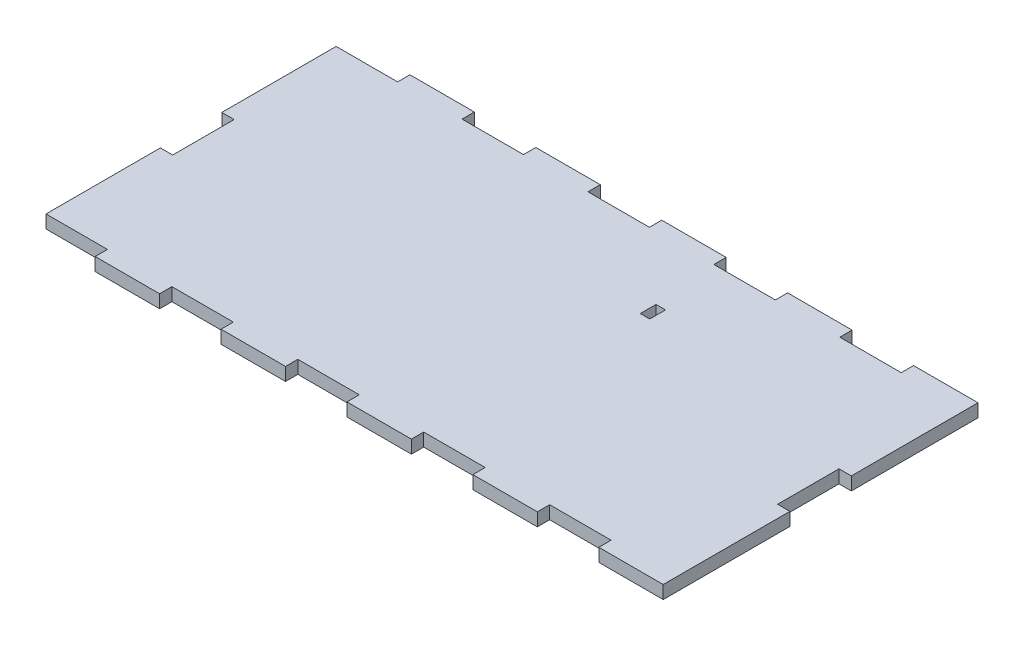
SolidWorks part; units mm, degrees
ref_plane "Front Plane" through (0, 0, 0) normal (0, 0, 1) x (1, 0, 0)
ref_plane "Top Plane" through (0, 0, 0) normal (0, 1, 0) x (1, 0, 0)
ref_plane "Right Plane" through (0, 0, 0) normal (1, 0, 0) x (0, 0, -1)
sketch "Sketch1" plane through (0, 0, 0) normal (0, 1, 0) x (1, 0, 0)
  line L1 (-100, 50) -> (100, 50)
  line L2 (-100, 50) -> (-100, -50)
  line L3 (-100, -50) -> (100, -50)
  line L4 (100, 50) -> (100, -50)
  line L5 (-100, 50) -> (100, -50) construction
  line L6 (-100, -50) -> (100, 50) construction
  point P0 (0, 0)
  dimension "Length" = 200
  dimension "with" = 100
extrude "Boss-Extrude1" add sketch "Sketch1" along normal blind 4.15
sketch "Sketch3" plane through (0, 4.15, 0) normal (0, 1, 0) x (1, 0, 0)
  line L0 (-100, 46.09) -> (-100, 50)
  line L1 (-100, -50) -> (-80.48, -50)
  line L2 (-100, -50) -> (-100, -46.09)
  line L3 (-100, -46.09) -> (-80.48, -46.09)
  line L4 (-80.48, -50) -> (-80.48, -46.09)
  line L5 (-100, 46.09) -> (-80.48, 46.09)
  line L6 (-80.48, 46.09) -> (-80.48, 50)
  line L7 (-100, 50) -> (-80.48, 50)
  line L8 (-60, 46.09) -> (-60, 50)
  line L9 (-60, 46.09) -> (-40.48, 46.09)
  line L10 (-40.48, 46.09) -> (-40.48, 50)
  line L11 (-60, 50) -> (-40.48, 50)
  line L12 (-20, 46.09) -> (-20, 50)
  line L13 (-20, 46.09) -> (-0.48, 46.09)
  line L14 (-0.48, 46.09) -> (-0.48, 50)
  line L15 (-20, 50) -> (-0.48, 50)
  line L16 (20, 46.09) -> (20, 50)
  line L17 (20, 46.09) -> (39.52, 46.09)
  line L18 (39.52, 46.09) -> (39.52, 50)
  line L19 (20, 50) -> (39.52, 50)
  line L20 (60, 46.09) -> (60, 50)
  line L21 (60, 46.09) -> (79.52, 46.09)
  line L22 (79.52, 46.09) -> (79.52, 50)
  line L23 (60, 50) -> (79.52, 50)
  line L24 (-60, -50) -> (-60, -46.09)
  line L25 (-60, -50) -> (-40.48, -50)
  line L26 (-40.48, -50) -> (-40.48, -46.09)
  line L27 (-60, -46.09) -> (-40.48, -46.09)
  line L28 (-20, -50) -> (-20, -46.09)
  line L29 (-20, -50) -> (-0.48, -50)
  line L30 (-0.48, -50) -> (-0.48, -46.09)
  line L31 (-20, -46.09) -> (-0.48, -46.09)
  line L32 (20, -50) -> (20, -46.09)
  line L33 (20, -50) -> (39.52, -50)
  line L34 (39.52, -50) -> (39.52, -46.09)
  line L35 (20, -46.09) -> (39.52, -46.09)
  line L36 (60, -50) -> (60, -46.09)
  line L37 (60, -50) -> (79.52, -50)
  line L38 (79.52, -50) -> (79.52, -46.09)
  line L39 (60, -46.09) -> (79.52, -46.09)
  line L40 (-100, -50) -> (100, -50) construction
  line L41 (100, 50) -> (-100, 50) construction
  point P5 (-80.48, -48.045)
  dimension "D1" = 3.91
  dimension "D2" = 19.52
  dimension "D5" = 20.48
  dimension "D3" = 2
  dimension "D4" = 5
extrude "Cut-Extrude2" cut sketch "Sketch3" against normal blind 10
sketch "Sketch4" plane through (0, 4.15, 0) normal (0, 1, 0) x (1, 0, 0)
  line L0 (-100, 9.76) -> (-100, -9.76)
  line L1 (-100, 9.76) -> (-96.09, 9.76)
  line L2 (-100, -9.76) -> (-96.09, -9.76)
  line L3 (-96.09, 9.76) -> (-96.09, -9.76)
  line L4 (-100, 46.09) -> (-100, -46.09) construction
  line L5 (0, -2.2825) -> (0, 2.2825) construction
  line L6 (100, -9.76) -> (96.09, -9.76)
  line L7 (96.09, 9.76) -> (96.09, -9.76)
  line L8 (100, 9.76) -> (96.09, 9.76)
  line L9 (100, 9.76) -> (100, -9.76)
  point P6 (-100, 0)
  dimension "D1" = 19.52
  dimension "D2" = 3.91
extrude "Cut-Extrude3" cut sketch "Sketch4" against normal blind 10
sketch "Sketch5" [suppressed] plane through (0, 4.15, 0) normal (0, 1, 0) x (1, 0, 0)
  line L0 (100, -36.09) -> (100, -40)
  line L1 (100, -36.09) -> (80.48, -36.09)
  line L2 (100, -40) -> (80.48, -40)
  line L3 (80.48, -36.09) -> (80.48, -40)
  line L4 (100, -40) -> (100, -9.76) construction
  line L5 (60, -36.09) -> (60, -40)
  line L6 (60, -36.09) -> (40.48, -36.09)
  line L7 (40.48, -36.09) -> (40.48, -40)
  line L8 (60, -40) -> (40.48, -40)
  line L9 (20, -36.09) -> (20, -40)
  line L10 (20, -36.09) -> (0.48, -36.09)
  line L11 (0.48, -36.09) -> (0.48, -40)
  line L12 (20, -40) -> (0.48, -40)
  line L13 (-20, -36.09) -> (-20, -40)
  line L14 (-20, -36.09) -> (-39.52, -36.09)
  line L15 (-39.52, -36.09) -> (-39.52, -40)
  line L16 (-20, -40) -> (-39.52, -40)
  line L17 (-60, -36.09) -> (-60, -40)
  line L18 (-60, -36.09) -> (-79.52, -36.09)
  line L19 (-79.52, -36.09) -> (-79.52, -40)
  line L20 (-60, -40) -> (-79.52, -40)
  line L21 (60, 40) -> (60, 36.09)
  line L22 (60, 40) -> (40.48, 40)
  line L23 (40.48, 40) -> (40.48, 36.09)
  line L24 (60, 36.09) -> (40.48, 36.09)
  line L25 (20, 40) -> (20, 36.09)
  line L26 (20, 40) -> (0.48, 40)
  line L27 (0.48, 40) -> (0.48, 36.09)
  line L28 (20, 36.09) -> (0.48, 36.09)
  line L29 (-20, 40) -> (-20, 36.09)
  line L30 (-20, 40) -> (-39.52, 40)
  line L31 (-39.52, 40) -> (-39.52, 36.09)
  line L32 (-20, 36.09) -> (-39.52, 36.09)
  line L33 (-60, 40) -> (-60, 36.09)
  line L34 (-60, 40) -> (-79.52, 40)
  line L35 (-79.52, 40) -> (-79.52, 36.09)
  line L36 (-60, 36.09) -> (-79.52, 36.09)
  line L37 (100, 40) -> (100, 36.09)
  line L38 (100, 40) -> (80.48, 40)
  line L39 (80.48, 40) -> (80.48, 36.09)
  line L40 (100, 36.09) -> (80.48, 36.09)
  line L41 (100, 40) -> (-100, 40) construction
  point P9 (100, 38.045)
  point P46 (100, -38.045)
  dimension "D1" = 3.91
  dimension "D2" = 19.52
  dimension "D5" = 20.48
  dimension "D3" = 5
  dimension "D4" = 2
extrude "Cut-Extrude4" [suppressed] cut sketch "Sketch5" against normal blind 10
sketch "Sketch6" [suppressed] plane through (0, 4.15, 0) normal (0, 1, 0) x (1, 0, 0)
  line L4 (-2.2825, 0) -> (2.2825, 0) construction
  line L5 (-40, -50) -> (-10.24, -50)
  line L6 (-40, -50) -> (-40, -46.09)
  line L7 (-40, -46.09) -> (-10.24, -46.09)
  line L8 (-10.24, -50) -> (-10.24, -46.09)
  line L9 (40, -50) -> (10.24, -50)
  line L10 (40, -50) -> (40, -46.09)
  line L11 (40, -46.09) -> (10.24, -46.09)
  line L12 (10.24, -50) -> (10.24, -46.09)
  line L13 (-40, 46.09) -> (-10.24, 46.09)
  line L14 (-10.24, 50) -> (-10.24, 46.09)
  line L15 (-40, 50) -> (-10.24, 50)
  line L16 (-40, 50) -> (-40, 46.09)
  line L17 (40, 46.09) -> (10.24, 46.09)
  line L18 (10.24, 50) -> (10.24, 46.09)
  line L19 (40, 50) -> (10.24, 50)
  line L20 (40, 50) -> (40, 46.09)
  line L21 (0, -2.2825) -> (0, 2.2825) construction
  line L22 (40, -46.09) -> (36.09, -46.09)
  line L23 (40, -46.09) -> (40, -10.24)
  line L24 (40, -10.24) -> (36.09, -10.24)
  line L25 (36.09, -46.09) -> (36.09, -10.24)
  line L26 (40, 46.09) -> (36.09, 46.09)
  line L27 (40, 46.09) -> (40, 10.24)
  line L28 (40, 10.24) -> (36.09, 10.24)
  line L29 (36.09, 46.09) -> (36.09, 10.24)
  line L30 (-40, 10.24) -> (-36.09, 10.24)
  line L31 (-36.09, 46.09) -> (-36.09, 10.24)
  line L32 (-40, 46.09) -> (-36.09, 46.09)
  line L33 (-40, 46.09) -> (-40, 10.24)
  line L34 (-40, -10.24) -> (-36.09, -10.24)
  line L35 (-36.09, -46.09) -> (-36.09, -10.24)
  line L36 (-40, -46.09) -> (-36.09, -46.09)
  line L37 (-40, -46.09) -> (-40, -10.24)
  dimension "D1" = 20.48
  dimension "D2" = 3.91
  dimension "D4" = 29.76
  dimension "D5" = 3.91
  dimension "D6" = 3.91
  dimension "D7" = 20.48
extrude "Cut-Extrude5" [suppressed] cut sketch "Sketch6" against normal blind 10
sketch "Sketch7" plane through (0, 4.15, 0) normal (0, 1, 0) x (1, 0, 0)
  line L0 (39.52, -46.09) -> (20, -46.09) construction
  line L1 (18.8, 13.91) -> (90, 13.91)
  line L2 (18.8, 13.91) -> (18.8, 37.91)
  line L3 (18.8, 37.91) -> (90, 37.91)
  line L4 (90, 13.91) -> (90, 37.91)
  line L5 (100, -50) -> (100, -9.76) construction
  dimension "D1" = 71.2
  dimension "D2" = 24
  dimension "D3" = 60
  dimension "D4" = 10
extrude "Cut-Extrude6" [suppressed] cut sketch "Sketch7" against normal blind 10
sketch "Sketch8" [suppressed] plane through (0, 4.15, 0) normal (0, 1, 0) x (1, 0, 0)
  line L0 (18.8, 37.91) -> (18.8, 13.91) construction
  line L1 (90, 13.91) -> (90, 37.91) construction
  line L4 (90, 37.91) -> (18.8, 37.91) construction
  line L5 (18.8, 13.91) -> (90, 13.91) construction
  circle A0 centre (16.9, 10.16) radius 1.5
  circle A1 centre (16.9, 41.66) radius 1.5
  circle A2 centre (91.9, 41.66) radius 1.5
  circle A3 centre (91.9, 10.16) radius 1.5
  dimension "D1" = 2
  dimension "D3" = 3
  dimension "D7" = 1.9
  dimension "D4" = 3.75
  dimension "D5" = 3.75
  dimension "D6" = 1.9
  dimension "D2" = 2
extrude "Cut-Extrude7" [suppressed] cut sketch "Sketch8" against normal blind 10
sketch "Sketch9" [suppressed] plane through (0, 4.15, 0) normal (0, 1, 0) x (1, 0, 0)
  line L0 (-0.48, -46.09) -> (-20, -46.09) construction
  line L1 (8.8, 3.91) -> (5.4, 3.91)
  line L2 (8.8, 3.91) -> (8.8, 42.91)
  line L3 (8.8, 42.91) -> (5.4, 42.91)
  line L4 (5.4, 3.91) -> (5.4, 42.91)
  line L5 (18.8, 37.91) -> (18.8, 13.91) construction
  dimension "D1" = 3.4
  dimension "D2" = 39
  dimension "D3" = 50
  dimension "D4" = 10
extrude "Cut-Extrude8" [suppressed] cut sketch "Sketch9" against normal blind 10
sketch "Sketch10" [suppressed] plane through (0, 4.15, 0) normal (0, 1, 0) x (1, 0, 0)
  line L1 (96.09, 9.76) -> (96.09, -9.76) construction
  line L3 (39.52, -46.09) -> (20, -46.09) construction
  circle A0 centre (26.09, 3.91) radius 3.425
  dimension "D1" = 6.85
  dimension "D2" = 50
  dimension "D3" = 70
extrude "Cut-Extrude9" [suppressed] cut sketch "Sketch10" against normal blind 10 contours A0
sketch "Sketch11" [suppressed] plane through (0, 4.15, 0) normal (0, 1, 0) x (1, 0, 0)
  line L1 (96.09, 9.76) -> (96.09, -9.76) construction
  line L4 (39.52, -46.09) -> (20, -46.09) construction
  circle A0 centre (41.09, 3.91) radius 3.125
  circle A1 centre (53.09, 3.91) radius 3.125
  dimension "D1" = 6.25
  dimension "D3" = 55
  dimension "D5" = 12
  dimension "D2" = 50
  dimension "D4" = 2
extrude "Cut-Extrude10" [suppressed] cut sketch "Sketch11" against normal blind 10
sketch "Sketch12" [suppressed] plane through (0, 4.15, 0) normal (0, 1, 0) x (1, 0, 0)
  line L1 (96.09, 9.76) -> (96.09, -9.76) construction
  line L2 (79.52, -46.09) -> (60, -46.09) construction
  circle A0 centre (68.09, 3.91) radius 3.825
  circle A1 centre (81.09, 3.91) radius 3.825
  dimension "D1" = 7.65
  dimension "D2" = 50
  dimension "D4" = 28
  dimension "D5" = 15
  dimension "D6" = 50
  dimension "D3" = 2
sketch "Sketch13" [suppressed] plane through (0, 4.15, 0) normal (0, 1, 0) x (1, 0, 0)
  line L0 (100, -50) -> (100, 50) construction
  line L1 (24.76, 50) -> (-24.76, 50)
  line L3 (24.76, 45.78) -> (-24.76, 45.78)
  line L4 (-24.76, 50) -> (-24.76, 45.78)
  line L5 (0, -2.2825) -> (0, 2.2825) construction
  line L6 (-100, 50) -> (-50.24, 50)
  line L8 (-95.78, 45.78) -> (-50.24, 45.78)
  line L9 (-50.24, 50) -> (-50.24, 45.78)
  line L10 (95.78, 45.78) -> (50.24, 45.78)
  line L11 (50.24, 50) -> (50.24, 45.78)
  line L12 (100, 50) -> (50.24, 50)
  line L14 (24.76, 50) -> (24.76, 45.78)
  line L15 (-100, 50) -> (-100, -50) construction
  line L21 (-100, -15.72) -> (-100, 15.72)
  line L22 (-100, 15.72) -> (-95.78, 15.72)
  line L23 (-95.78, -15.72) -> (-95.78, 15.72)
  line L24 (-2.2825, 0) -> (2.2825, 0) construction
  line L26 (-100, 50) -> (-100, 30.24)
  line L27 (-100, 30.24) -> (-95.78, 30.24)
  line L28 (-95.78, 45.78) -> (-95.78, 30.24)
  line L29 (-100, -15.72) -> (-95.78, -15.72)
  line L30 (-100, -30.24) -> (-95.78, -30.24)
  line L31 (-95.78, -50) -> (-95.78, -30.24)
  line L32 (-100, -50) -> (-95.78, -50)
  line L33 (-100, -50) -> (-100, -30.24)
  line L34 (100, 30.24) -> (95.78, 30.24)
  line L35 (95.78, 45.78) -> (95.78, 30.24)
  line L37 (100, 50) -> (100, 30.24)
  line L38 (100, -15.72) -> (100, 15.72)
  line L39 (100, 15.72) -> (95.78, 15.72)
  line L40 (95.78, -15.72) -> (95.78, 15.72)
  line L41 (100, -15.72) -> (95.78, -15.72)
  line L42 (100, -50) -> (100, -30.24)
  line L43 (100, -50) -> (95.78, -50)
  line L44 (95.78, -50) -> (95.78, -30.24)
  line L45 (100, -30.24) -> (95.78, -30.24)
  line L46 (-100, -50) -> (100, -50) construction
  line L47 (100, 50) -> (-100, 50) construction
  dimension "D1" = 4.22
  dimension "D2" = 49.76
  dimension "D3" = 25.48
  dimension "D4" = 4.22
  dimension "D5" = 19.76
  dimension "D6" = 4.22
  dimension "D7" = 4.22
  dimension "D8" = 14.52
  dimension "D9" = 31.44
extrude "Cut-Extrude12" [suppressed] cut sketch "Sketch13" against normal blind 10
sketch "Sketch14" [suppressed] plane through (0, 4.15, 0) normal (0, 1, 0) x (1, 0, 0)
  line L0 (95.78, -30.24) -> (95.78, -50) construction
  line L1 (-96.02, -50) -> (95.78, -50)
  line L2 (-96.02, -50) -> (-96.02, -45.78)
  line L3 (-96.02, -45.78) -> (95.78, -45.78)
  line L4 (95.78, -50) -> (95.78, -45.78)
  dimension "D1" = 4.22
extrude "Cut-Extrude13" [suppressed] cut sketch "Sketch14" against normal blind 10
sketch "Sketch15" [suppressed] plane through (0, 4.15, 0) normal (0, 1, 0) x (1, 0, 0)
  line L0 (10.24, 50) -> (-10.24, 50) construction
  line L1 (2.35, 30) -> (-1.63, 30)
  line L2 (2.35, 30) -> (2.35, 15.48)
  line L3 (2.35, 15.48) -> (-1.63, 15.48)
  line L4 (-1.63, 30) -> (-1.63, 15.48)
  line L5 (2.35, 30) -> (-1.63, 15.48) construction
  line L6 (2.35, 15.48) -> (-1.63, 30) construction
  line L7 (36.09, 46.09) -> (36.09, 10.24) construction
  line L9 (-2.2825, 0) -> (2.2825, 0) construction
  line L10 (2.35, -15.48) -> (-1.63, -15.48)
  line L11 (-1.63, -30) -> (-1.63, -15.48)
  line L12 (2.35, -30) -> (-1.63, -30)
  line L13 (2.35, -30) -> (2.35, -15.48)
  point P0 (0.36, 22.74)
  dimension "D1" = 20
  dimension "D2" = 14.52
  dimension "D3" = 33.74
  dimension "D4" = 3.98
extrude "Cut-Extrude14" [suppressed] cut sketch "Sketch15" against normal blind 10
sketch "Sketch16" [suppressed] plane through (0, 4.15, 0) normal (0, 1, 0) x (1, 0, 0)
  line L1 (-25.24, 2.195) -> (-50.48, 2.195)
  line L2 (-25.24, 2.195) -> (-25.24, -2.195)
  line L3 (-25.24, -2.195) -> (-50.48, -2.195)
  line L4 (-50.48, 2.195) -> (-50.48, -2.195)
  line L5 (-25.24, 2.195) -> (-50.48, -2.195) construction
  line L6 (-25.24, -2.195) -> (-50.48, 2.195) construction
  line L8 (0, -2.2825) -> (0, 2.2825) construction
  line L9 (25.24, -2.195) -> (50.48, -2.195)
  line L10 (50.48, 2.195) -> (50.48, -2.195)
  line L11 (25.24, 2.195) -> (50.48, 2.195)
  line L12 (25.24, 2.195) -> (25.24, -2.195)
  line L13 (-25.24, -36.09) -> (-25.24, 36.09) construction
  line L14 (-20, -36.09) -> (-39.52, -36.09) construction
  line L15 (-39.52, 36.09) -> (-20, 36.09) construction
  line L16 (-100, 40) -> (-100, 9.76) construction
  point P0 (-37.86, 0)
  point P5 (-25.24, 0)
  point P6 (-25.24, 0)
  point P7 (25.24, 0)
  dimension "D1" = 4.39
  dimension "D2" = 49.52
  dimension "D3" = 25.24
extrude "Cut-Extrude15" [suppressed] cut sketch "Sketch16" against normal blind 10
sketch "Sketch17" [suppressed] plane through (0, 4.15, 0) normal (0, 1, 0) x (1, 0, 0)
  line L1 (50.24, 45.78) -> (95.78, 45.78) construction
  line L2 (-24.76, 45.78) -> (24.76, 45.78) construction
  line L3 (95.78, 15.72) -> (95.78, -15.72) construction
  circle A0 centre (85.78, 10.48) radius 1.5
  circle A1 centre (34.98, 25.78) radius 1.5
  circle A2 centre (85.78, -17.42) radius 1.5
  circle A3 centre (33.38, -22.52) radius 1.5
  dimension "D7" = 3
  dimension "D8" = 3
  dimension "D9" = 3
  dimension "D10" = 3
  dimension "D11" = 10
  dimension "D12" = 10
  dimension "D1" = 35.3
  dimension "D2" = 20
  dimension "D3" = 50.8
  dimension "D4" = 27.9
  dimension "D5" = 52.4
  dimension "D6" = 48.3
extrude "Cut-Extrude16" [suppressed] cut sketch "Sketch17" against normal blind 10
sketch "Sketch18" [suppressed] plane through (0, 4.15, 0) normal (0, 1, 0) x (1, 0, 0)
  line L0 (95.78, 15.72) -> (95.78, -15.72) construction
  line L1 (7.78, 37.5) -> (27.78, 37.5)
  line L3 (7.78, -31.78) -> (27.78, -31.78)
  line L4 (27.78, 37.5) -> (27.78, -31.78)
  line L5 (7.78, 2.5) -> (7.78, -31.78)
  line L6 (7.78, 37.5) -> (-7.22, 37.5)
  line L10 (95.78, -45.78) -> (-95.78, -45.78) construction
  line L11 (-24.76, 45.78) -> (24.76, 45.78) construction
  line L14 (7.78, 2.5) -> (-7.22, 2.5)
  line L15 (-7.22, 37.5) -> (-7.22, 2.5)
  dimension "D1" = 20
  dimension "D2" = 8.28
  dimension "D3" = 68
  dimension "D4" = 14
  dimension "D5" = 15
  dimension "D6" = 35
  dimension "D7" = 20
extrude "Cut-Extrude18" [suppressed] cut sketch "Sketch18" against normal blind 10
sketch "Sketch19" [suppressed] plane through (0, 4.15, 0) normal (0, 1, 0) x (1, 0, 0)
  line L0 (5.4, 42.91) -> (5.4, 3.91) construction
  line L1 (-2.1, 25.91) -> (0.9, 25.91)
  line L2 (-2.1, 25.91) -> (-2.1, 20.91)
  line L3 (-2.1, 20.91) -> (0.9, 20.91)
  line L4 (0.9, 25.91) -> (0.9, 20.91)
  line L5 (-2.1, 25.91) -> (0.9, 20.91) construction
  line L6 (-2.1, 20.91) -> (0.9, 25.91) construction
  point P0 (-0.6, 23.41)
  point P7 (5.4, 23.41)
  point P8 (0.9, 23.41)
  dimension "D1" = 4.5
  dimension "D2" = 3
  dimension "D4" = 5
extrude "Cut-Extrude19" [suppressed] cut sketch "Sketch19" against normal blind 4.2
sketch "Sketch20" [suppressed] plane through (0, 4.15, 0) normal (0, 1, 0) x (1, 0, 0)
  line L0 (100, -30.24) -> (100, -15.72) construction
  line L1 (-1.85, -18.28) -> (1.15, -18.28)
  line L2 (-1.85, -18.28) -> (-1.85, -23.28)
  line L3 (-1.85, -23.28) -> (1.15, -23.28)
  line L4 (1.15, -18.28) -> (1.15, -23.28)
  line L5 (-1.85, -18.28) -> (1.15, -23.28) construction
  line L6 (-1.85, -23.28) -> (1.15, -18.28) construction
  line L8 (95.78, -45.78) -> (-95.78, -45.78) construction
  point P0 (-0.35, -20.78)
  dimension "D1" = 22.5
  dimension "D2" = 98.85
  dimension "D3" = 3
  dimension "D4" = 5
extrude "Cut-Extrude21" [suppressed] cut sketch "Sketch20" against normal blind 4.2
sketch "Sketch21" plane through (0, 4.15, 0) normal (0, 1, 0) x (1, 0, 0)
  line L0 (100, 9.76) -> (100, 50) construction
  line L1 (21.81, 25.91) -> (24.81, 25.91)
  line L2 (21.81, 25.91) -> (21.81, 20.91)
  line L3 (21.81, 20.91) -> (24.81, 20.91)
  line L4 (24.81, 25.91) -> (24.81, 20.91)
  line L5 (21.81, 25.91) -> (24.81, 20.91) construction
  line L6 (21.81, 20.91) -> (24.81, 25.91) construction
  line L8 (-0.48, -46.09) -> (-20, -46.09) construction
  point P0 (23.31, 23.41)
  dimension "D1" = 3
  dimension "D2" = 5
  dimension "D3" = 75.19
  dimension "D4" = 67
extrude "Cut-Extrude22" cut sketch "Sketch21" against normal blind 4.2
sketch "Sketch22" [suppressed] plane through (0, 4.15, 0) normal (0, 1, 0) x (1, 0, 0)
  line L1 (-24.76, 45.78) -> (24.76, 45.78) construction
  line L2 (-95.78, -15.72) -> (-95.78, 15.72) construction
  circle A0 centre (-78.55, -14.22) radius 1.5
  circle A1 centre (-7.22, -14.22) radius 1.5
  dimension "D1" = 3
  dimension "D2" = 3
  dimension "D3" = 71.33
  dimension "D4" = 17.23
  dimension "D5" = 60
extrude "Cut-Extrude23" [suppressed] cut sketch "Sketch22" against normal blind 10
extrude "Cut-Extrude24" [suppressed] cut sketch "Sketch12" against normal blind 10
equation "\"kerf\"=0.24"
equation "\"D5@Sketch5\"=20 + 2*\"kerf\""
